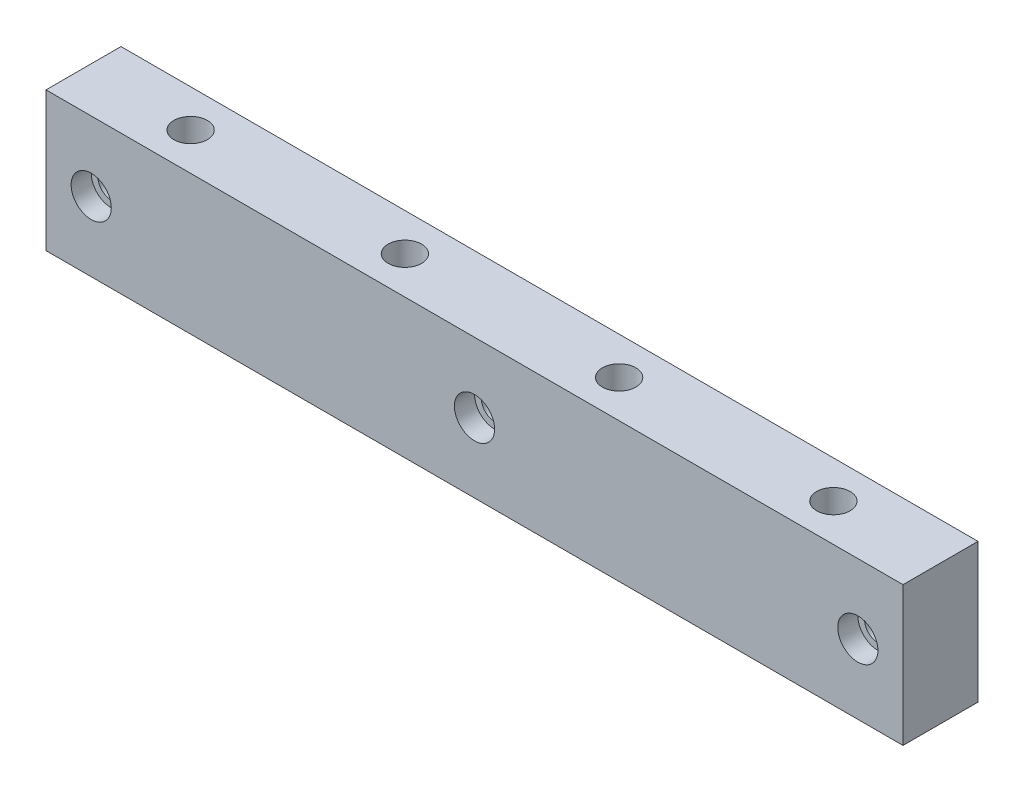
SolidWorks part; units mm, degrees
material "7075-T6 (SN)"
ref_plane "X-Y Datum" through (0, 0, 0) normal (0, 0, 1) x (1, 0, 0)
ref_plane "X-Z Datum" through (0, 0, 0) normal (0, 1, 0) x (1, 0, 0)
ref_plane "Y-Z Datum" through (0, 0, 0) normal (1, 0, 0) x (0, 0, -1)
sketch "Sketch1" plane through (0, 0, 0) normal (0, 1, 0) x (1, 0, 0)
  line L0 (101.6, 8.89) -> (76.2, 8.89) construction
  line L1 (101.6, 17.78) -> (-101.6, 17.78)
  line L2 (101.6, 17.78) -> (101.6, 0)
  line L3 (101.6, 0) -> (-101.6, 0)
  line L4 (-101.6, 17.78) -> (-101.6, 0)
  line L7 (76.2, 8.89) -> (25.4, 8.89) construction
  line L8 (25.4, 8.89) -> (-25.4, 8.89) construction
  line L9 (-25.4, 8.89) -> (-76.2, 8.89) construction
  line L10 (-76.2, 8.89) -> (-101.6, 8.89) construction
  circle A0 centre (76.2, 8.89) radius 3.9688
  circle A1 centre (25.4, 8.89) radius 3.9687
  circle A2 centre (-25.4, 8.89) radius 3.9687
  circle A3 centre (-76.2, 8.89) radius 3.9688
  point P0 (0, 0)
  point P19 (0, 8.89)
  dimension "D3" = 7.9375
  dimension "D1" = 203.2
  dimension "D2" = 17.78
  dimension "D4" = 50.8
  dimension "D5" = 25.4
extrude "Boss-Extrude1" add sketch "Sketch1" against normal blind 33.02
sketch "Sketch2" plane through (0, 0, 0) normal (0, 0, 1) x (1, 0, 0)
  line L0 (80.1687, 0) -> (80.1687, -33.02) construction
  line L1 (-101.6, 0) -> (101.6, 0) construction
  line L2 (-101.6, -33.02) -> (101.6, -33.02) construction
  line L3 (72.2312, 0) -> (72.2312, -33.02) construction
  line L4 (-72.2313, 0) -> (-72.2313, -33.02) construction
  line L5 (-80.1687, 0) -> (-80.1687, -33.02) construction
  line L6 (80.1687, 0) -> (72.2312, 0) construction
  line L7 (80.1687, 0) -> (72.2312, 0) construction
  line L8 (-72.2313, 0) -> (-80.1687, 0) construction
  line L9 (-72.2312, 0) -> (-80.1688, 0) construction
  line L10 (101.6, -16.51) -> (80.1687, -16.51) construction
  line L12 (101.6, -33.02) -> (101.6, 0) construction
  line L13 (-80.1687, -16.51) -> (-101.6, -16.51) construction
  line L14 (-101.6, -33.02) -> (-101.6, 0) construction
  circle A0 centre (90.8844, -16.51) radius 3.175
  circle A1 centre (0, -16.51) radius 3.175
  circle A2 centre (-90.8844, -16.51) radius 3.175
  point P12 (76.2, 0)
  point P15 (-76.2, 0)
  point P33 (-90.8844, -16.51)
  point P34 (90.8844, -16.51)
  dimension "D3" = 6.35
  dimension "D1" = 7.9375
  dimension "D2" = 7.9375
extrude "Cut-Extrude1" cut sketch "Sketch2" against normal up to surface (17.78 mm away) up to face at (0, -16.51, -17.78)
sketch "Sketch3" plane through (0, 0, 0) normal (0, 0, 1) x (1, 0, 0)
  circle A0 centre (90.8844, -16.51) radius 4.7625
  circle A1 centre (0, -16.51) radius 4.7625
  circle A2 centre (-90.8844, -16.51) radius 4.7625
  dimension "D1" = 9.525
extrude "Cut-Extrude2" cut sketch "Sketch3" against normal blind 4.7752
ref_plane "Plane1" through (0, -16.51, 0) normal (0, 1, 0) x (1, 0, 0)
ref_point "Point1"
ref_point "Point2"
ref_point "Point3"
ref_point "Point4"
